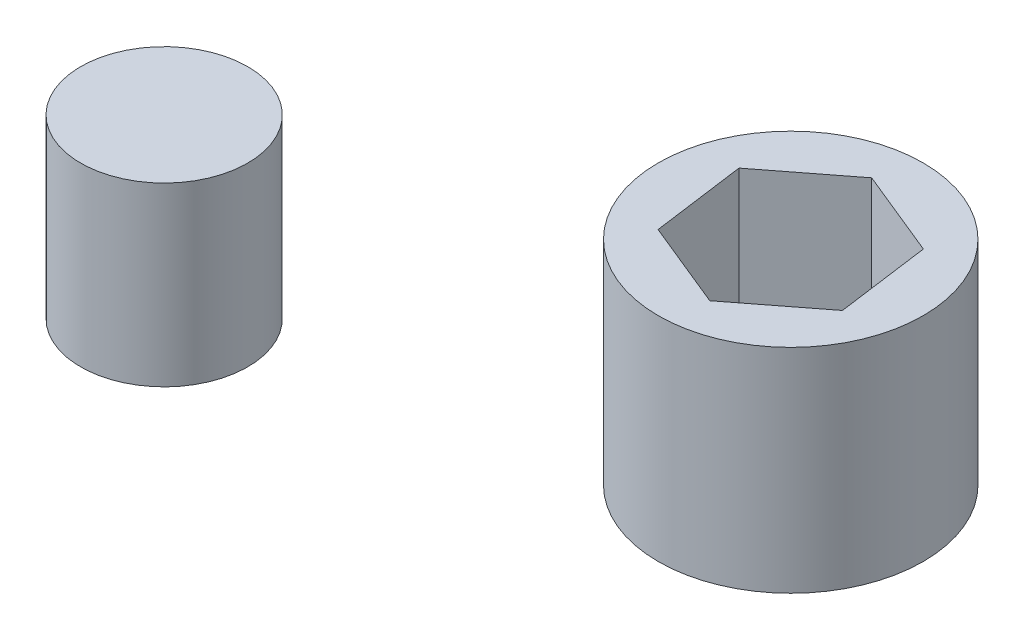
SolidWorks part; units mm, degrees
ref_plane "Front Plane" through (0, 0, 0) normal (0, 0, 1) x (1, 0, 0)
ref_plane "Top Plane" through (0, 0, 0) normal (0, 1, 0) x (1, 0, 0)
ref_plane "Right Plane" through (0, 0, 0) normal (1, 0, 0) x (0, 0, -1)
sketch "Sketch1" plane through (0, 0, 0) normal (0, 0, 1) x (1, 0, 0)
  line L1 (0, 0) -> (31.4984, 0)
  line L2 (0, 0) -> (0, 66.521)
  line L3 (0, 66.521) -> (31.4984, 66.521)
  line L4 (31.4984, 0) -> (31.4984, 66.521)
revolve "Revolve1" add sketch "Sketch1" angle 360 about L2
sketch "Sketch2" plane through (0, 0, 0) normal (0, 1, 0) x (1, 0, 0)
  line L1 (205.4077, 50.2274) -> (200.6012, 85.5404)
  line L2 (200.6012, 85.5404) -> (167.616, 99.0343)
  line L3 (167.616, 99.0343) -> (139.4373, 77.2153)
  line L4 (139.4373, 77.2153) -> (144.2438, 41.9023)
  line L5 (144.2438, 41.9023) -> (177.229, 28.4084)
  line L6 (177.229, 28.4084) -> (205.4077, 50.2274)
  circle A0 centre (172.4225, 63.7214) radius 49.9075
  circle A1 centre (172.4225, 63.7214) radius 30.8639 construction
extrude "Boss-Extrude1" add sketch "Sketch2" along normal blind 80.264 separate body
